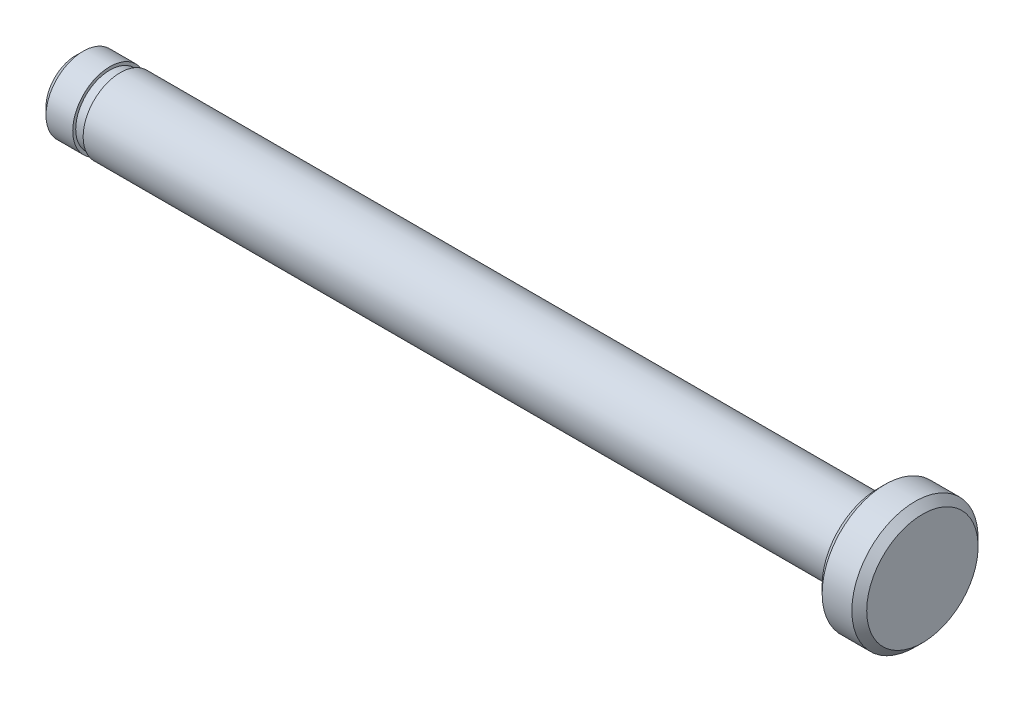
SolidWorks part; units mm, degrees
ref_plane "Front Plane" through (0, 0, 0) normal (0, 0, 1) x (1, 0, 0)
ref_plane "Top Plane" through (0, 0, 0) normal (0, 1, 0) x (1, 0, 0)
ref_plane "Right Plane" through (0, 0, 0) normal (1, 0, 0) x (0, 0, -1)
sketch "Sketch1" plane through (0, 0, 0) normal (0, 1, 0) x (1, 0, 0)
  line L0 (-28.5, 0) -> (28.5, 0)
  line L1 (28.5, 0) -> (28.5, 3.75)
  line L2 (28, 4.25) -> (26, 4.25)
  line L3 (25.5, 3.75) -> (25.5, 2.5)
  line L4 (25.5, 2.5) -> (-25.5, 2.5)
  line L5 (-25.5, 2.5) -> (-25.5, 2.3)
  line L6 (-25.5, 2.3) -> (-26.2, 2.3)
  line L7 (-26.2, 2.3) -> (-26.2, 2.5)
  line L8 (-26.2, 2.5) -> (-28, 2.5)
  line L9 (-28.5, 2) -> (-28.5, 0)
  line L10 (-28, 2.5) -> (-28.5, 2)
  line L11 (28.5, 3.75) -> (28, 4.25)
  line L12 (26, 4.25) -> (25.5, 3.75)
  point P4 (0, 0)
  point P6 (28.5, 4.25)
  point P7 (25.5, 4.25)
  point P13 (-28.5, 2.5)
  dimension "D1" = 2.5
  dimension "D2" = 54
  dimension "D3" = 3
  dimension "D4" = 4.25
  dimension "D5" = 0.7
  dimension "D6" = 2.3
  dimension "D7" = 51
revolve "Revolve1" add sketch "Sketch1" angle 360 about L0
